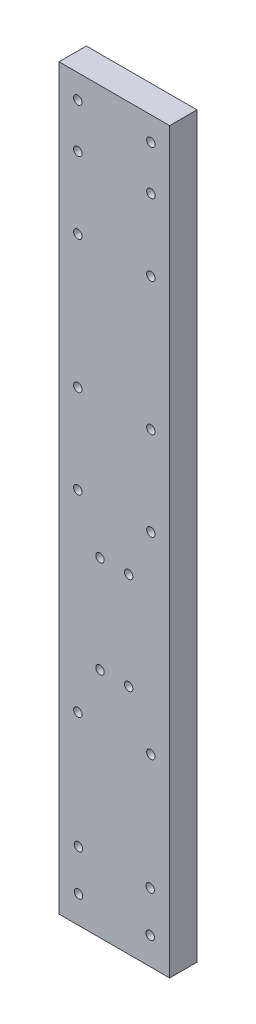
SolidWorks part; units mm, degrees
ref_plane "Front Plane" through (0, 0, 0) normal (0, 0, 1) x (1, 0, 0)
ref_plane "Top Plane" through (0, 0, 0) normal (0, 1, 0) x (1, 0, 0)
ref_plane "Right Plane" through (0, 0, 0) normal (1, 0, 0) x (0, 0, -1)
sketch "Sketch1" plane through (0, 0, 0) normal (0, 0, 1) x (1, 0, 0)
  line L0 (16.2, 0) -> (16.2, 108.14)
  line L1 (16.2, 108.14) -> (0, 108.14)
  line L2 (0, 108.14) -> (0, 0)
  line L3 (0, 0) -> (16.2, 0)
  line L4 (16.2, 57.71) -> (0, 57.71) construction
  line L5 (0, 12.5) -> (16.2, 12.5) construction
  line L6 (0, 24.5) -> (16.2, 24.5) construction
  line L7 (0, 90.16) -> (16.2, 90.16) construction
  line L8 (0, 65.71) -> (16.2, 65.71) construction
  line L9 (8.1, 108.14) -> (8.1, 96.16) construction
  line L11 (0, 96.16) -> (16.2, 96.16) construction
  circle A0 centre (13.45, 55.21) radius 0.62
  circle A1 centre (10.2, 48.21) radius 0.62
  circle A2 centre (13.45, 104.66) radius 0.62
  circle A3 centre (2.75, 98.16) radius 0.62
  circle A4 centre (6, 48.21) radius 0.62
  circle A5 centre (2.75, 27) radius 0.62
  circle A6 centre (2.75, 87.66) radius 0.62
  circle A7 centre (2.75, 55.21) radius 0.62
  circle A8 centre (13.45, 87.66) radius 0.62
  circle A9 centre (13.45, 98.16) radius 0.62
  circle A28 centre (13.45, 68.21) radius 0.62
  circle A29 centre (6, 34) radius 0.62
  circle A32 centre (2.75, 104.66) radius 0.62
  circle A33 centre (10.2, 34) radius 0.62
  circle A34 centre (2.75, 68.21) radius 0.62
  circle A35 centre (13.45, 27) radius 0.62
  circle A36 centre (2.85, 10) radius 0.62
  circle A37 centre (13.35, 10) radius 0.62
  circle A38 centre (13.35, 4) radius 0.62
  circle A39 centre (2.85, 4) radius 0.62
  dimension "D45" = 1.24
  dimension "D1" = 4
  dimension "D2" = 4
  dimension "D3" = 2.85
  dimension "D4" = 2.85
  dimension "D5" = 16.2
  dimension "D6" = 6
  dimension "D7" = 6
  dimension "D8" = 2.85
  dimension "D9" = 2.85
  dimension "D10" = 2.5
  dimension "D11" = 12
  dimension "D12" = 33.21
  dimension "D13" = 2.5
  dimension "D14" = 2.5
  dimension "D15" = 2.75
  dimension "D16" = 2.75
  dimension "D17" = 2.5
  dimension "D18" = 2.5
  dimension "D19" = 2.75
  dimension "D20" = 2.75
  dimension "D21" = 9.5
  dimension "D22" = 6
  dimension "D23" = 9.5
  dimension "D24" = 6
  dimension "D25" = 9.5
  dimension "D26" = 9.5
  dimension "D27" = 6
  dimension "D28" = 6
  dimension "D29" = 8
  dimension "D30" = 24.45
  dimension "D31" = 2.5
  dimension "D32" = 2.5
  dimension "D33" = 2.75
  dimension "D34" = 2.75
  dimension "D35" = 6
  dimension "D36" = 2.75
  dimension "D37" = 2
  dimension "D38" = 2.75
  dimension "D39" = 8.5
  dimension "D40" = 11.98
  dimension "D41" = 2.5
  dimension "D42" = 2.5
  dimension "D43" = 2.75
  dimension "D44" = 2.75
extrude "Boss-Extrude1" add sketch "Sketch1" along normal blind 4
equation "\"D12@Sketch1\"= \"HL@parametersSketch@prostheticParameters.SLDPRT\" * 0.266 - 12 - 4 'Middle PIP Length"
equation "\"D30@Sketch1\"= \"HL@parametersSketch@prostheticParameters.SLDPRT\" * 0.17 - 4 - 3'Middle MIP Length"
equation "\"D5@Sketch1\"= \"fingerWidth@parametersSketch@prostheticParameters.SLDPRT\" 'Middle Width"
equation "\"D40@Sketch1\"= \"HL@parametersSketch@prostheticParameters.SLDPRT\" * 0.108 - 3 - 5'Middle DIP Length"
equation "\"D45@Sketch1\"= 1.04 + \"tol1@parametersSketch@prostheticParameters.SLDPRT\""
